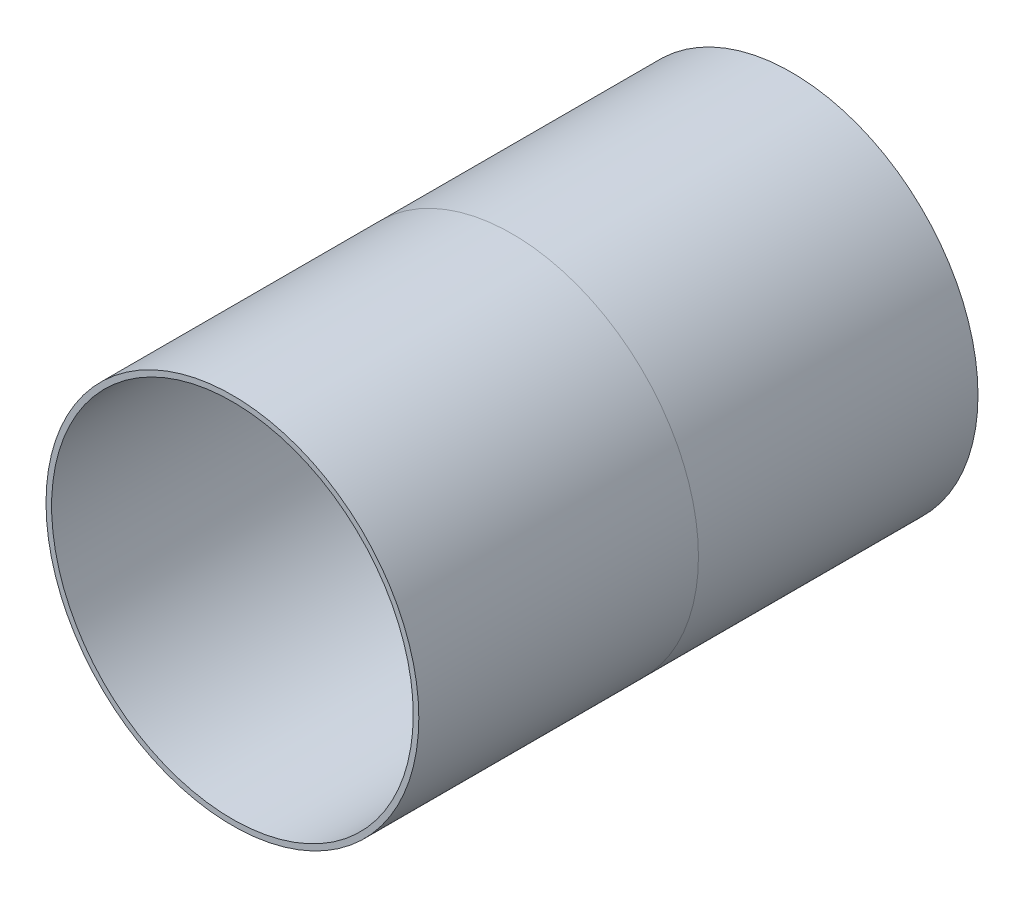
SolidWorks part; units mm, degrees
ref_plane "Plan de face" through (0, 0, 0) normal (0, 0, 1) x (1, 0, 0)
ref_plane "Plan de dessus" through (0, 0, 0) normal (0, 1, 0) x (1, 0, 0)
ref_plane "Plan de droite" through (0, 0, 0) normal (1, 0, 0) x (0, 0, -1)
sketch "Esquisse2" plane through (0, 0, 0) normal (0, 0, 1) x (1, 0, 0)
  circle A0 centre (0, 0) radius 76.1746
  circle A1 centre (0, 0) radius 73.914
  dimension "D1" = 152.3492
  dimension "D2" = 147.828
extrude "Boss.-Extru.1" add sketch "Esquisse2" along normal blind 114.3
sketch "Esquisse3" plane through (0, 0, 114.3) normal (0, 0, 1) x (1, 0, 0)
  circle A0 centre (0, 0) radius 76.2
  circle A1 centre (0, 0) radius 73.914
  dimension "D1" = 147.828
extrude "Boss.-Extru.2" add sketch "Esquisse3" along normal blind 114.3
